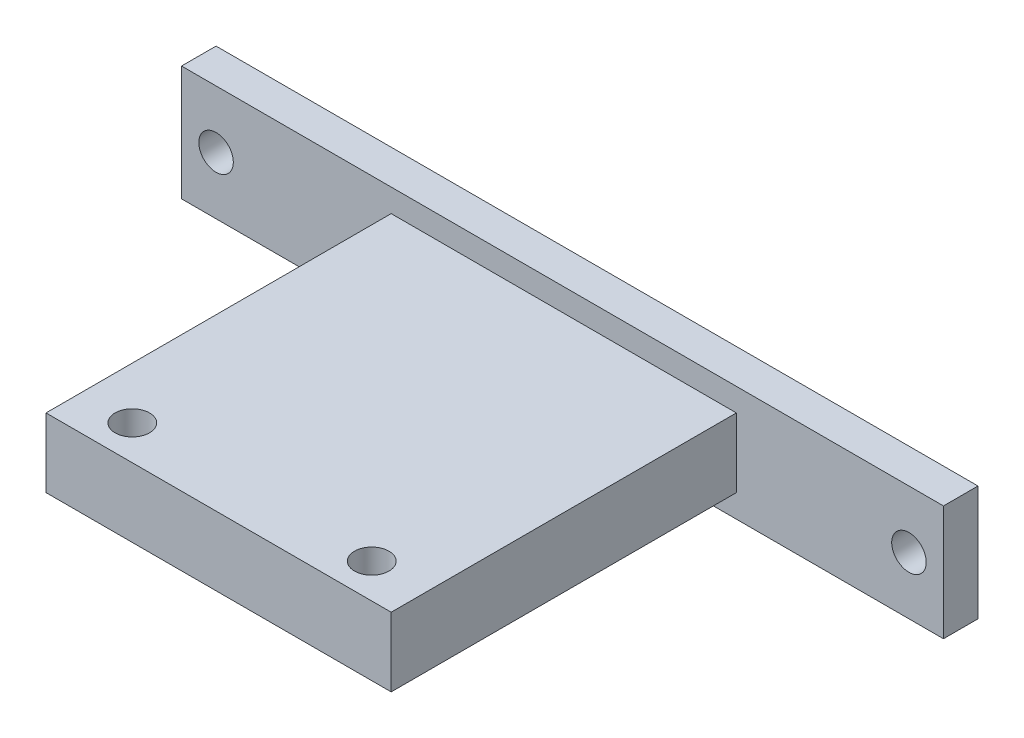
SolidWorks part; units mm, degrees
ref_plane "Front Plane" through (0, 0, 0) normal (0, 0, 1) x (1, 0, 0)
ref_plane "Top Plane" through (0, 0, 0) normal (0, 1, 0) x (1, 0, 0)
ref_plane "Right Plane" through (0, 0, 0) normal (1, 0, 0) x (0, 0, -1)
sketch "Sketch1" plane through (0, 0, 0) normal (0, 0, 1) x (1, 0, 0)
  line L1 (0, 0) -> (60.22, 0)
  line L2 (0, 0) -> (0, 10)
  line L3 (0, 10) -> (60.22, 10)
  line L4 (60.22, 0) -> (60.22, 10)
  line L5 (0, 10) -> (-3, 10)
  line L6 (0, 10) -> (0, 0)
  line L7 (0, 0) -> (-3, 0)
  line L8 (-3, 10) -> (-3, 0)
  line L9 (60.22, 0) -> (63.22, 0)
  line L10 (60.22, 0) -> (60.22, 10)
  line L11 (60.22, 10) -> (63.22, 10)
  line L12 (63.22, 0) -> (63.22, 10)
  circle A0 centre (0, 5) radius 1.5
  circle A1 centre (60.22, 5) radius 1.5
  dimension "D3" = 3
  dimension "D4" = 3
  dimension "D1" = 60.22
  dimension "D2" = 10
  dimension "D5" = 3
  dimension "D6" = 3
extrude "Boss-Extrude1" add sketch "Sketch1" along normal blind 3 contours A0 L2 L5 L8 L7 | A1 L4 L3 L2 A0 L1 | A1 L4 L9 L12 L11
ref_plane "Plane1" through (0, 5, 0) normal (0, 1, 0) x (1, 0, 0)
sketch "Sketch2" plane through (0, 5, 0) normal (0, 1, 0) x (1, 0, 0)
  line L0 (63.22, -3) -> (-3, -3) construction
  line L1 (15.22, -3) -> (45.22, -3)
  line L2 (15.22, -3) -> (15.22, -33)
  line L3 (15.22, -33) -> (45.22, -33)
  line L4 (45.22, -3) -> (45.22, -33)
  line L5 (63.22, -3) -> (63.22, 0) construction
  dimension "D1" = 30
  dimension "D2" = 30
  dimension "D3" = 18
extrude "Boss-Extrude2" add sketch "Sketch2" along normal blind 3 and the other way blind 3
sketch "Sketch3" plane through (0, 2, 0) normal (0, -1, 0) x (1, 0, 0)
  line L0 (15.22, 33) -> (45.22, 33) construction
  line L1 (15.22, 3) -> (15.22, 33) construction
  circle A0 centre (19.72, 30) radius 1.5
  circle A1 centre (40.53, 30) radius 1.5
  point P6 (0, 0)
  point P9 (0, 0)
  dimension "D1" = 3
  dimension "D2" = 3
  dimension "D3" = 3
  dimension "D4" = 20.81
  dimension "D5" = 4.5
extrude "Cut-Extrude1" cut sketch "Sketch3" against normal through all
